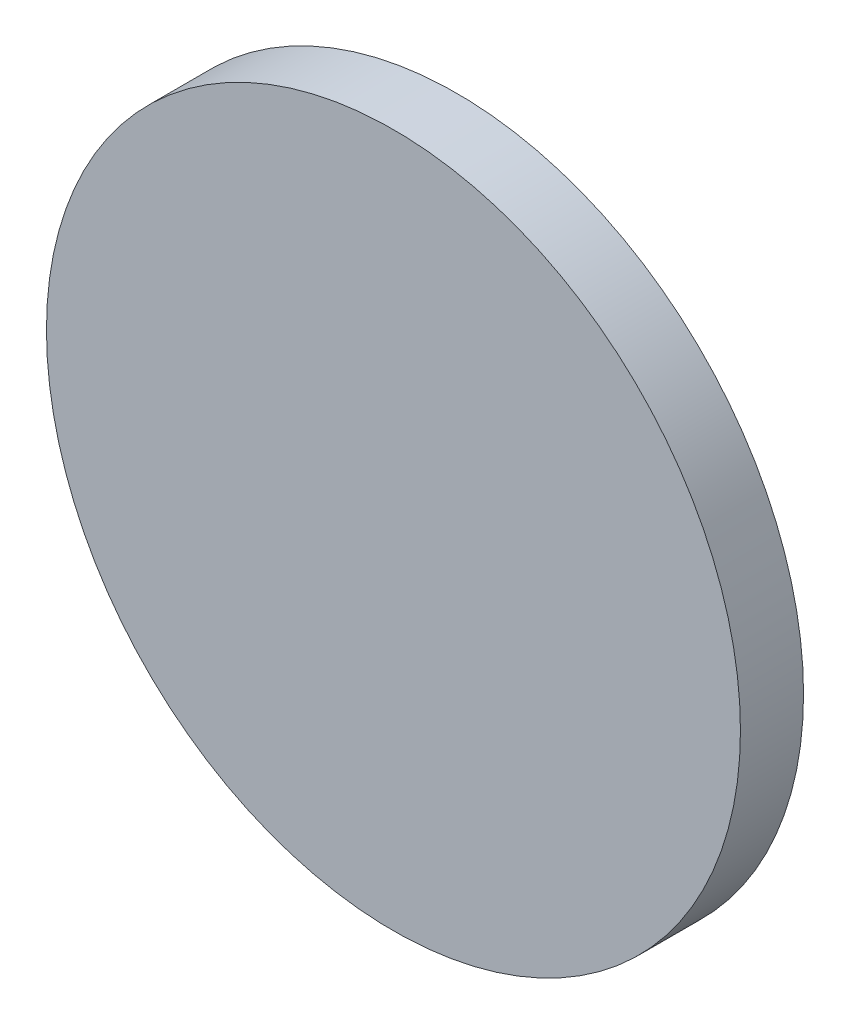
SolidWorks part; units mm, degrees
ref_plane "Face" through (0, 0, 0) normal (0, 0, 1) x (1, 0, 0)
ref_plane "Dessus" through (0, 0, 0) normal (0, 1, 0) x (1, 0, 0)
ref_plane "Droite" through (0, 0, 0) normal (1, 0, 0) x (0, 0, -1)
sketch "Esquisse1" plane through (0, 0, 0) normal (0, 0, 1) x (1, 0, 0)
  circle A0 centre (0, 0) radius 11
  dimension "D1" = 22
extrude "Base-Extrusion" add sketch "Esquisse1" along normal blind 2
